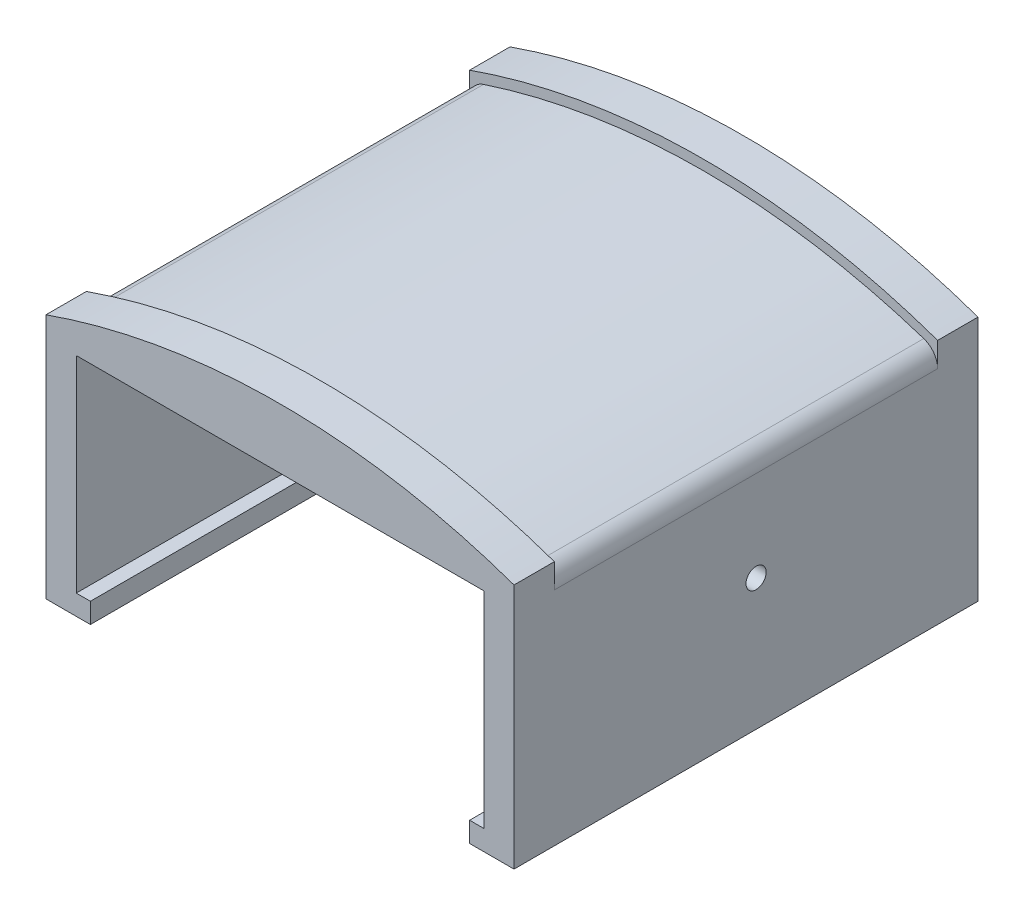
SolidWorks part; units mm, degrees
material "Polyester Resin"
ref_plane "Front Plane" through (0, 0, 0) normal (0, 0, 1) x (1, 0, 0)
ref_plane "Top Plane" through (0, 0, 0) normal (0, 1, 0) x (1, 0, 0)
ref_plane "Right Plane" through (0, 0, 0) normal (1, 0, 0) x (0, 0, -1)
sketch "Sketch1" plane through (0, 0, 0) normal (0, 0, 1) x (1, 0, 0)
  line L0 (-25.654, 0) -> (25.654, 0)
  line L1 (-25.654, 0) -> (-25.654, -25.908)
  line L2 (25.654, 0) -> (25.654, -25.908)
  line L3 (-25.654, -25.908) -> (-23.876, -25.908)
  line L4 (-23.876, -25.908) -> (-23.876, -28.448)
  line L5 (-23.876, -28.448) -> (-29.464, -28.448)
  line L6 (-29.464, -28.448) -> (-29.464, 1.27)
  line L7 (25.654, -25.908) -> (23.876, -25.908)
  line L8 (23.876, -25.908) -> (23.876, -28.448)
  line L9 (23.876, -28.448) -> (29.464, -28.448)
  line L10 (29.464, -28.448) -> (29.464, 1.27)
  arc A0 (-29.464, 1.27) -> (29.464, 1.27) centre (0, -82.6054) cw
  point P3 (0, 0)
  dimension "D10" = 88.9
  dimension "D11" = 1.778
  dimension "D1" = 51.308
  dimension "D2" = 25.908
  dimension "D3" = 25.908
  dimension "D4" = 2.54
  dimension "D5" = 5.588
  dimension "D6" = 1.27
  dimension "D7" = 2.54
  dimension "D8" = 5.588
  dimension "D9" = 1.27
  dimension "D12" = 1.778
extrude "Boss-Extrude1" add sketch "Sketch1" along normal mid plane 50.8
sketch "Sketch2" plane through (0, 0, 25.4) normal (0, 0, 1) x (1, 0, 0)
  line L0 (29.464, -28.448) -> (29.464, 2.54)
  line L1 (-29.464, -28.448) -> (-29.464, 2.54)
  line L11 (-25.654, -25.908) -> (-25.654, 0)
  line L12 (-25.654, 0) -> (25.654, 0)
  line L13 (25.654, 0) -> (25.654, -25.908)
  line L14 (25.654, -25.908) -> (23.876, -25.908)
  line L15 (23.876, -25.908) -> (23.876, -28.448)
  line L16 (23.876, -28.448) -> (29.464, -28.448)
  line L17 (29.464, -28.448) -> (29.464, 1.27)
  line L18 (-29.464, 1.27) -> (-29.464, -28.448)
  line L19 (-29.464, -28.448) -> (-23.876, -28.448)
  line L20 (-23.876, -28.448) -> (-23.876, -25.908)
  line L21 (-23.876, -25.908) -> (-25.654, -25.908)
  line L22 (-25.654, -25.908) -> (-25.654, 0)
  line L23 (-25.654, 0) -> (25.654, 0)
  line L24 (25.654, 0) -> (25.654, -25.908)
  line L25 (25.654, -25.908) -> (23.876, -25.908)
  line L26 (23.876, -25.908) -> (23.876, -28.448)
  line L27 (23.876, -28.448) -> (29.464, -28.448)
  line L30 (-29.464, -28.448) -> (-23.876, -28.448)
  line L31 (-23.876, -28.448) -> (-23.876, -25.908)
  line L32 (-23.876, -25.908) -> (-25.654, -25.908)
  arc A0 (-29.464, 2.54) -> (29.464, 2.54) centre (0, -81.3354) cw
  arc A1 (29.464, 1.27) -> (-29.464, 1.27) centre (0, -82.6054) ccw
  dimension "D2" = 1.27
  dimension "D4" = 88.9
  dimension "D3" = 1.27
  dimension "D1" = 0
extrude "Boss-Extrude2" add sketch "Sketch2" along normal blind 5.08
pattern_linear "LPattern1" count 2 spacing 53.34 along (0, 0, -1) of "Boss-Extrude2"
fillet "Fillet7" radius 2.54 2 edges at (29.464, 1.27, 1.27) (-29.464, 1.27, 1.27)
sketch "Sketch4" plane through (-29.464, 0, 0) normal (-1, 0, 0) x (0, 0, 1)
  line L0 (30.48, -28.448) -> (-27.94, -28.448) construction
  line L1 (0, -19.6428) -> (0, 19.6428) construction
  circle A0 centre (0, -11.938) radius 1.27
  dimension "D1" = 2.54
  dimension "D2" = 16.51
extrude "Cut-Extrude1" cut sketch "Sketch4" against normal through all
